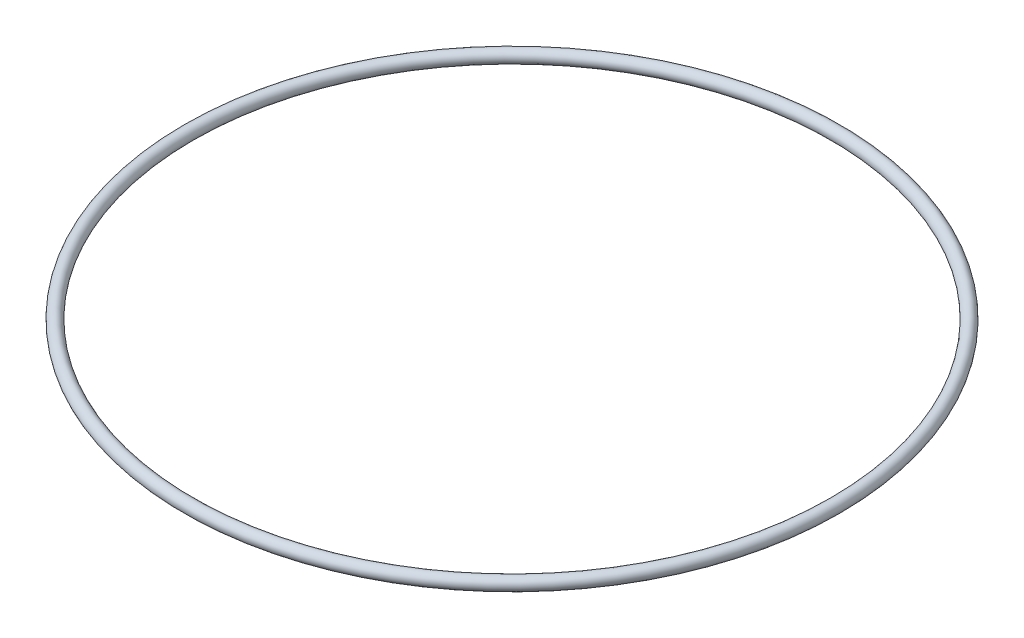
SolidWorks part; units mm, degrees
material "Silicon Rubber"
ref_plane "Front" through (0, 0, 0) normal (0, 0, 1) x (1, 0, 0)
ref_plane "Top" through (0, 0, 0) normal (0, 1, 0) x (1, 0, 0)
ref_plane "Right" through (0, 0, 0) normal (1, 0, 0) x (0, 0, -1)
sketch "Sketch2" plane through (0, 0, 0) normal (0, 0, 1) x (1, 0, 0)
  line L0 (0, -1.7066) -> (0, 1.7066) construction
  circle A0 centre (-20.4, 0) radius 0.4
  point P4 (0, 0)
  dimension "D1" = 0.8
  dimension "D2" = 40
revolve "Revolve1" add sketch "Sketch2" angle 360 about L0
